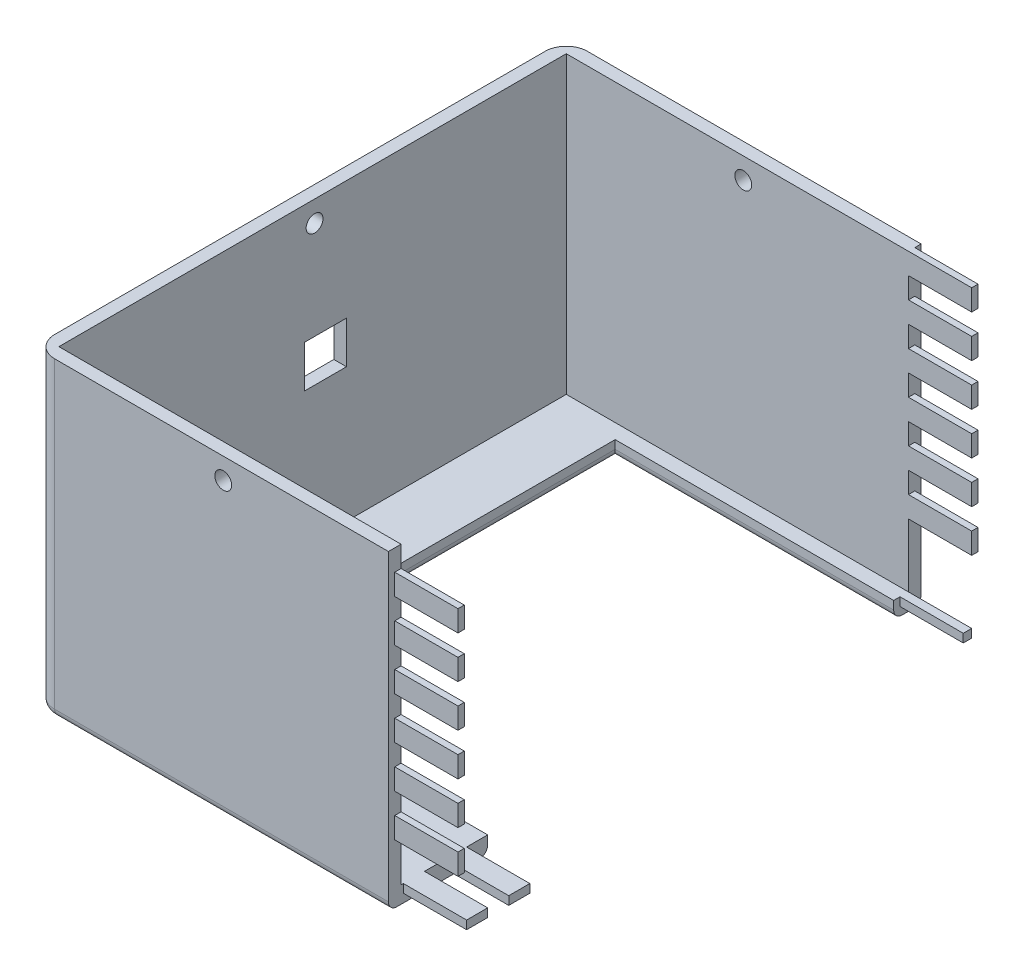
SolidWorks part; units mm, degrees
ref_plane "Front Plane" through (0, 0, 0) normal (0, 0, 1) x (1, 0, 0)
ref_plane "Top Plane" through (0, 0, 0) normal (0, 1, 0) x (1, 0, 0)
ref_plane "Right Plane" through (0, 0, 0) normal (1, 0, 0) x (0, 0, -1)
sketch "Sketch1" plane through (0, 0, 0) normal (0, 1, 0) x (1, 0, 0)
  line L0 (-76.7346, 32.1468) -> (-76.7346, 52.1468)
  line L2 (-76.7346, 32.1468) -> (-76.7346, -68.2432)
  line L3 (-76.7346, -68.2432) -> (60.5554, -68.2432)
  line L6 (-79.7346, 55.1468) -> (88.645, 55.1468)
  line L7 (-76.7346, 52.1468) -> (85.645, 52.1468)
  line L9 (85.645, 52.1468) -> (85.645, -68.2432)
  line L10 (85.645, -68.2432) -> (60.5554, -68.2432)
  line L11 (-79.7346, 55.1468) -> (-79.7346, -71.2432)
  line L12 (-79.7346, -71.2432) -> (88.645, -71.2432)
  line L13 (88.645, 55.1468) -> (88.645, -71.2432)
  dimension "D1" = 100.39
  dimension "D2" = 137.29
  dimension "D3" = 20
  dimension "D5" = 3
  dimension "D6" = 3
  dimension "D7" = 3
  dimension "D8" = 3
extrude "Boss-Extrude1" add sketch "Sketch1" along normal blind 70
sketch "Sketch2" plane through (0, 0, 0) normal (0, -1, 0) x (-1, 0, 0)
  line L1 (79.7346, -71.2432) -> (-88.645, -71.2432)
  line L2 (79.7346, -71.2432) -> (79.7346, 55.1468)
  line L3 (79.7346, 55.1468) -> (-88.645, 55.1468)
  line L4 (-88.645, -71.2432) -> (-88.645, 55.1468)
extrude "Boss-Extrude2" add sketch "Sketch2" along normal blind 4
sketch "Sketch3" plane through (0, 0, 0) normal (0, 1, 0) x (1, 0, 0)
  line L0 (85.645, -68.2432) -> (85.645, 52.1468) construction
  line L1 (81.145, -47.6932) -> (-61.6346, -47.6932)
  line L2 (81.145, -47.6932) -> (81.145, 48.6468)
  line L3 (81.145, 48.6468) -> (-61.6346, 48.6468)
  line L4 (-61.6346, -47.6932) -> (-61.6346, 48.6468)
  line L5 (85.645, 52.1468) -> (-76.7346, 52.1468) construction
  line L6 (-76.7346, -68.2432) -> (85.645, -68.2432) construction
  line L7 (-76.7346, 52.1468) -> (-76.7346, -68.2432) construction
  dimension "D1" = 4.5
  dimension "D2" = 3.5
  dimension "D3" = 20.55
  dimension "D4" = 15.1
extrude "Cut-Extrude1" cut sketch "Sketch3" against normal blind 4
fillet "Fillet1" radius 5 4 edges at (-79.7346, 33, 71.2432) (-79.7346, 33, -55.1468) (88.645, 33, -55.1468) (88.645, 33, 71.2432)
fillet "Fillet4" radius 2 8 edges at (87.1805, -4, -53.6823) (4.4552, -4, -55.1468) (-78.2701, -4, -53.6823) (-79.7346, -4, 8.0482) (-78.2701, -4, 69.7787) (4.4552, -4, 71.2432) (87.1805, -4, 69.7787) (88.645, -4, 8.0482)
fillet "Fillet5" radius 2 4 edges at (-61.6346, -4, -0.4768) (9.7552, -4, -48.6468) (81.145, -4, -0.4768) (9.7552, -4, 47.6932)
sketch "Sketch4" plane through (-79.7346, 0, 0) normal (-1, 0, 0) x (0, 0, 1)
  line L1 (0.0087, 41.7497) -> (10.0087, 41.7497)
  line L2 (0.0087, 41.7497) -> (0.0087, 31.7497)
  line L3 (0.0087, 31.7497) -> (10.0087, 31.7497)
  line L4 (10.0087, 41.7497) -> (10.0087, 31.7497)
  line L5 (0.0087, 41.7497) -> (10.0087, 31.7497) construction
  line L6 (0.0087, 31.7497) -> (10.0087, 41.7497) construction
  point P0 (5.0087, 36.7497)
  dimension "D1" = 10
extrude "Cut-Extrude2" cut sketch "Sketch4" against normal blind 195
sketch "Sketch6" plane through (88.645, 0, 0) normal (1, 0, 0) x (0, 0, -1)
  line L0 (-66.2432, 70) -> (50.1468, 70) construction
  circle A0 centre (-7.5756, 65) radius 2
  dimension "D1" = 5
extrude "Cut-Extrude3" cut sketch "Sketch6" against normal blind 195
sketch "Sketch8" plane through (0, 0, -55.1468) normal (0, 0, -1) x (-1, 0, 0)
  line L0 (-83.645, 70) -> (74.7346, 70) construction
  line L1 (-83.645, 70) -> (-83.645, -2) construction
  line L2 (74.7346, -2) -> (74.7346, 70) construction
  circle A0 centre (-43.645, 65) radius 2
  circle A1 centre (34.7346, 65) radius 2
  dimension "D3" = 40
  dimension "D1" = 5
  dimension "D2" = 5
  dimension "D4" = 40
extrude "Cut-Extrude4" cut sketch "Sketch8" against normal blind 195
sketch "Sketch12" plane through (0, 0, 0) normal (0, 0, 1) x (1, 0, 0)
  line L0 (-74.7346, 70) -> (83.645, 70) construction
  line L1 (4.4552, 70) -> (91.6364, 70)
  line L2 (4.4552, 70) -> (4.4552, -10.3652)
  line L3 (4.4552, -10.3652) -> (91.6364, -10.3652)
  line L4 (91.6364, 70) -> (91.6364, -10.3652)
extrude "Cut-Extrude5" cut sketch "Sketch12" against normal through all both and the other way through all
sketch "Sketch14" plane through (4.4552, 0, 0) normal (1, 0, 0) x (0, 0, -1)
  line L0 (52.1468, 0) -> (-68.2432, 0) construction
  line L1 (-52.6932, 0) -> (-57.6932, 0)
  line L2 (-52.6932, 0) -> (-52.6932, -2)
  line L3 (-52.6932, -2) -> (-57.6932, -2)
  line L4 (-57.6932, 0) -> (-57.6932, -2)
  line L5 (-47.6932, -2) -> (-47.6932, 0) construction
  line L7 (-67.6932, 0) -> (-62.6932, 0)
  line L8 (-67.6932, 0) -> (-67.6932, -2)
  line L9 (-67.6932, -2) -> (-62.6932, -2)
  line L10 (-62.6932, 0) -> (-62.6932, -2)
  dimension "D1" = 5
  dimension "D2" = 2
  dimension "D3" = 5
  dimension "D4" = 2
  dimension "D5" = 5
  dimension "D6" = 5
extrude "Boss-Extrude4" add sketch "Sketch14" along normal blind 15
sketch "Sketch17" plane through (4.4552, 0, 0) normal (1, 0, 0) x (0, 0, -1)
  line L1 (52.1468, 0) -> (50.1468, 0)
  line L2 (52.1468, 0) -> (52.1468, -2)
  line L3 (52.1468, -2) -> (50.1468, -2)
  line L4 (50.1468, 0) -> (50.1468, -2)
  dimension "D1" = 2
extrude "Boss-Extrude5" add sketch "Sketch17" along normal up to surface (15 mm away) up to face at (19.4552, -1, 65.1932)
sketch "Sketch18" plane through (4.4552, 0, 0) normal (1, 0, 0) x (0, 0, -1)
  line L0 (-68.2432, 70) -> (-68.2432, 0) construction
  line L1 (-68.2432, 65) -> (-69.7432, 65)
  line L2 (-68.2432, 65) -> (-68.2432, 60)
  line L3 (-68.2432, 60) -> (-69.7432, 60)
  line L4 (-69.7432, 65) -> (-69.7432, 60)
  line L5 (-68.2432, 70) -> (-71.2432, 70) construction
  line L6 (-68.2432, 55) -> (-69.7432, 55)
  line L7 (-69.7432, 55) -> (-69.7432, 50)
  line L8 (-68.2432, 55) -> (-68.2432, 50)
  line L9 (-68.2432, 50) -> (-69.7432, 50)
  line L10 (-68.2432, 45) -> (-69.7432, 45)
  line L11 (-69.7432, 45) -> (-69.7432, 40)
  line L12 (-68.2432, 45) -> (-68.2432, 40)
  line L13 (-68.2432, 40) -> (-69.7432, 40)
  line L14 (-68.2432, 35) -> (-69.7432, 35)
  line L15 (-69.7432, 35) -> (-69.7432, 30)
  line L16 (-68.2432, 35) -> (-68.2432, 30)
  line L17 (-68.2432, 30) -> (-69.7432, 30)
  line L18 (-68.2432, 25) -> (-69.7432, 25)
  line L19 (-69.7432, 25) -> (-69.7432, 20)
  line L20 (-68.2432, 25) -> (-68.2432, 20)
  line L21 (-68.2432, 20) -> (-69.7432, 20)
  line L22 (-68.2432, 15) -> (-69.7432, 15)
  line L23 (-69.7432, 15) -> (-69.7432, 10)
  line L24 (-68.2432, 15) -> (-68.2432, 10)
  line L25 (-68.2432, 10) -> (-69.7432, 10)
  line L30 (-68.2432, 5) -> (-69.7432, 5) [skipped]
  line L31 (-69.7432, 5) -> (-69.7432, 0) [skipped]
  line L32 (-68.2432, 5) -> (-68.2432, 0) [skipped]
  line L33 (-68.2432, 0) -> (-69.7432, 0) [skipped]
  line L34 (-8.0482, 156.2147) -> (-8.0482, -16.2147) construction
  point P31 (-8.0482, 70)
  dimension "D1" = 5
  dimension "D2" = 5
  dimension "D3" = 1.5
  dimension "D4" = 7
extrude "Boss-Extrude8" add sketch "Sketch18" along normal blind 15
sketch "Sketch19" plane through (4.4552, 0, 0) normal (1, 0, 0) x (0, 0, -1)
  line L0 (52.1468, 60) -> (53.6468, 60)
  line L1 (52.1468, 70) -> (53.6468, 70)
  line L2 (52.1468, 70) -> (52.1468, 65)
  line L3 (52.1468, 65) -> (53.6468, 65)
  line L4 (53.6468, 70) -> (53.6468, 65)
  line L5 (52.1468, 60) -> (52.1468, 55)
  line L6 (52.1468, 55) -> (53.6468, 55)
  line L7 (53.6468, 60) -> (53.6468, 55)
  line L8 (52.1468, 50) -> (53.6468, 50)
  line L9 (52.1468, 50) -> (52.1468, 45)
  line L10 (52.1468, 45) -> (53.6468, 45)
  line L11 (53.6468, 50) -> (53.6468, 45)
  line L12 (52.1468, 40) -> (53.6468, 40)
  line L13 (52.1468, 40) -> (52.1468, 35)
  line L14 (52.1468, 35) -> (53.6468, 35)
  line L15 (53.6468, 40) -> (53.6468, 35)
  line L16 (52.1468, 30) -> (53.6468, 30)
  line L17 (52.1468, 30) -> (52.1468, 25)
  line L18 (52.1468, 25) -> (53.6468, 25)
  line L19 (53.6468, 30) -> (53.6468, 25)
  line L20 (52.1468, 20) -> (53.6468, 20)
  line L21 (52.1468, 20) -> (52.1468, 15)
  line L22 (52.1468, 15) -> (53.6468, 15)
  line L23 (53.6468, 20) -> (53.6468, 15)
  dimension "D1" = 1.5
  dimension "D2" = 5
  dimension "D3" = 6
extrude "Boss-Extrude9" add sketch "Sketch19" along normal blind 15
